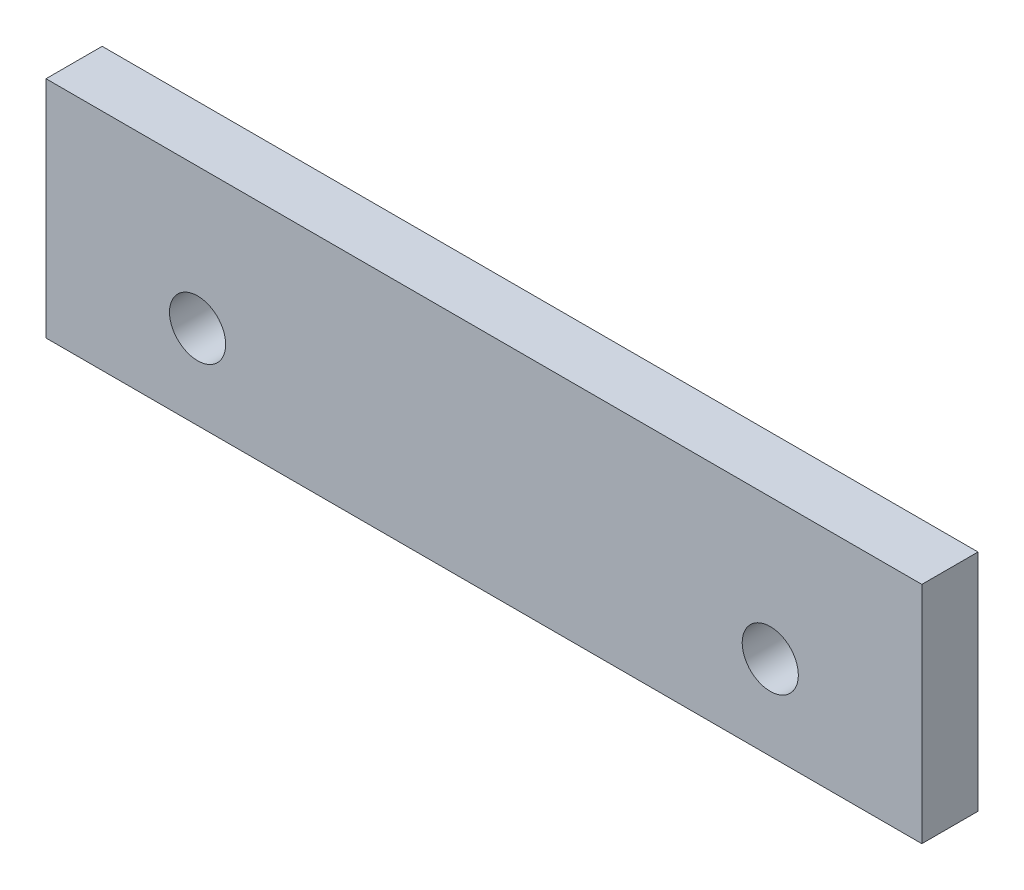
SolidWorks part; units mm, degrees
ref_plane "Front Plane" through (0, 0, 0) normal (0, 0, 1) x (1, 0, 0)
ref_plane "Top Plane" through (0, 0, 0) normal (0, 1, 0) x (1, 0, 0)
ref_plane "Right Plane" through (0, 0, 0) normal (1, 0, 0) x (0, 0, -1)
sketch "Sketch1" plane through (0, 0, 0) normal (0, 0, 1) x (1, 0, 0)
  line L1 (-39, 10) -> (39, 10)
  line L2 (-39, 10) -> (-39, -10)
  line L3 (-39, -10) -> (39, -10)
  line L4 (39, 10) -> (39, -10)
  dimension "D1" = 20
  dimension "D2" = 78
  dimension "D3" = 39
  dimension "D4" = 10
extrude "Boss-Extrude1" add sketch "Sketch1" along normal blind 5
sketch "Sketch3" plane through (0, 0, 0) normal (0, 0, -1) x (-1, 0, 0)
  line L0 (-39, 10) -> (39, 10) construction
  line L1 (-39, -10) -> (-39, 10) construction
  circle A1 centre (-25.5, -2.5) radius 2.5
  circle A3 centre (25.5, -2.5) radius 2.5
  point P8 (0, 0)
  point P9 (0, 0)
  dimension "D3" = 5
  dimension "D5" = 5
  dimension "D1" = 12.5
  dimension "D2" = 13.5
  dimension "D4" = 51
extrude "Cut-Extrude1" cut sketch "Sketch3" against normal blind 10
